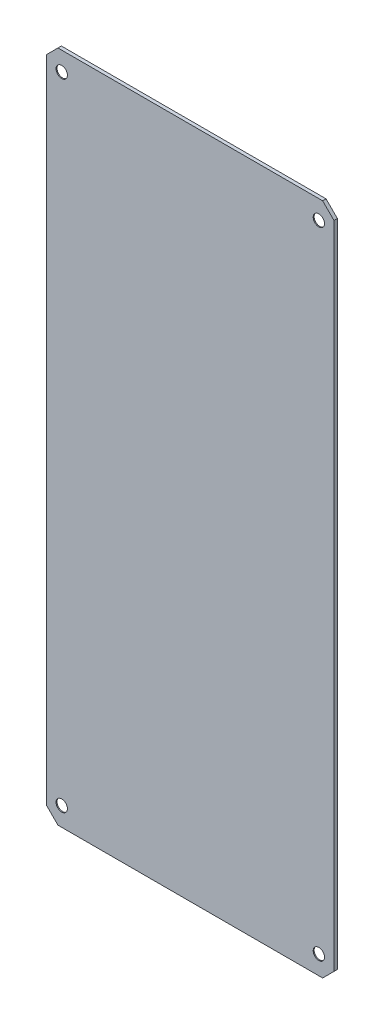
SolidWorks part; units mm, degrees
ref_plane "Front Plane" through (0, 0, 0) normal (0, 0, 1) x (1, 0, 0)
ref_plane "Top Plane" through (0, 0, 0) normal (0, 1, 0) x (1, 0, 0)
ref_plane "Right Plane" through (0, 0, 0) normal (1, 0, 0) x (0, 0, -1)
sketch "Sketch2" plane through (0, 0, 0) normal (0, 0, 1) x (1, 0, 0)
  line L8 (3, 178) -> (-5.559, 178) construction
  line L9 (0, 175) -> (0, 179.9048) construction
  line L10 (76, 3) -> (76, 0) construction
  line L11 (76, 0) -> (53, 0) construction
  line L13 (0, 178) -> (76, 178)
  line L14 (0, 178) -> (0, 0)
  line L15 (0, 0) -> (76, 0)
  line L16 (76, 178) -> (76, 0)
  point P0 (0, 0)
  point P1 (56, 200)
  point P2 (0, 178)
  dimension "D2" = 178
  dimension "D3" = 76
extrude "Boss-Extrude1" add sketch "Sketch2" along normal blind 0.9
sketch "Sketch4" plane through (0, 0, 0.9) normal (0, 0, 1) x (1, 0, 0)
  line L2 (38, 178) -> (38, 0) construction
  line L4 (0, 0) -> (76, 0) construction
  line L6 (76, 178) -> (0, 178) construction
  line L7 (0, 178) -> (0, 0) construction
  line L8 (0, 89) -> (76, 89) construction
  line L9 (76, 0) -> (76, 178) construction
  circle A0 centre (4, 173) radius 2.667
  circle A4 centre (72, 173) radius 2.667
  circle A5 centre (72, 5) radius 2.667
  circle A6 centre (4, 5) radius 2.667
  dimension "D1" = 5
  dimension "D2" = 4
extrude "Cut-Extrude1" cut sketch "Sketch4" against normal blind 2
sketch "Sketch5" plane through (0, 0, 0.9) normal (0, 0, 1) x (1, 0, 0)
  line L0 (38, 178) -> (38, 0) construction
  line L3 (76, 178) -> (0, 178) construction
  line L6 (0, 0) -> (76, 0) construction
  line L7 (0, 89) -> (76, 89) construction
  line L8 (0, 178) -> (0, 0) construction
  line L9 (76, 0) -> (76, 178) construction
  circle A6 centre (4, 5) radius 2.667
  circle A7 centre (4, 5) radius 1.5
  circle A8 centre (4, 173) radius 1.5
  circle A9 centre (4, 173) radius 2.667
  circle A10 centre (72, 5) radius 1.5
  circle A11 centre (72, 5) radius 2.667
  circle A12 centre (72, 173) radius 2.667
  circle A13 centre (72, 173) radius 1.5
extrude "Boss-Extrude2" add sketch "Sketch5" against normal blind 0.254
chamfer "Chamfer1" distance 3 angle 45 4 edges at (0, 0, 0.45) (76, 0, 0.45) (76, 178, 0.45) (0, 178, 0.45)
